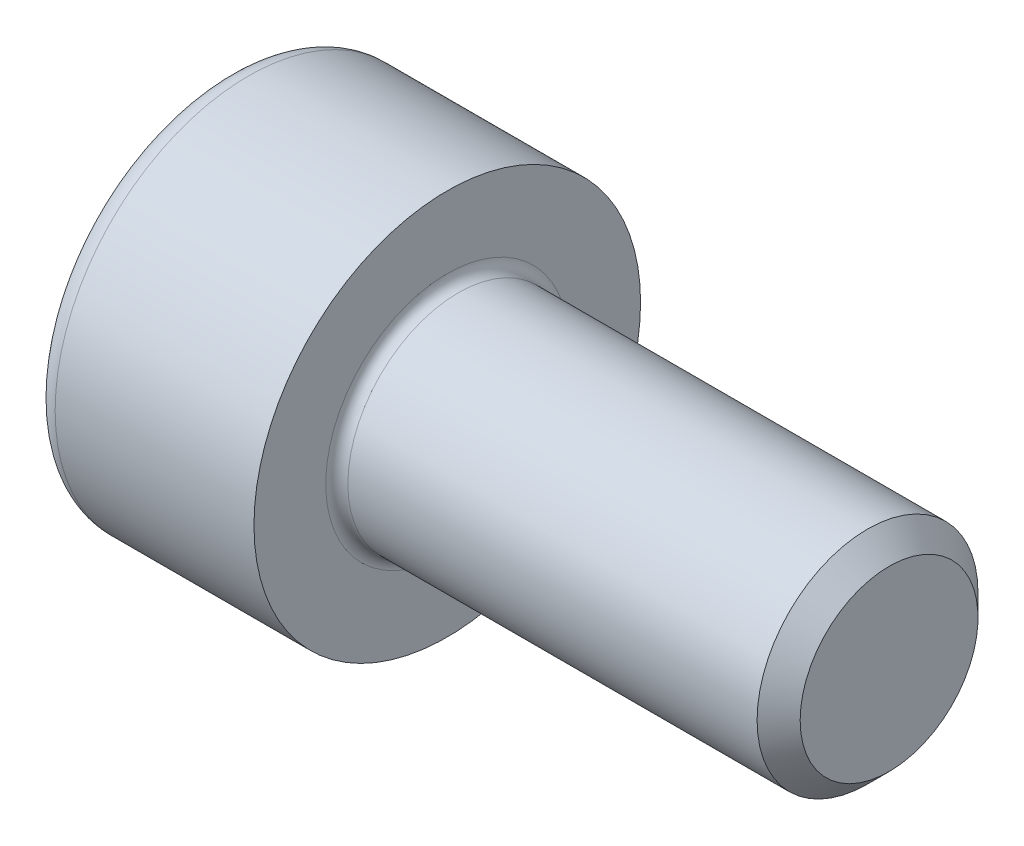
SolidWorks part; units mm, degrees
material "Ст3пс ГОСТ 380-2005"
ref_plane "Plane1" through (0, 0, 0) normal (0, 0, 1) x (1, 0, 0)
ref_plane "Plane2" through (0, 0, 0) normal (0, 1, 0) x (1, 0, 0)
ref_plane "Plane3" through (0, 0, 0) normal (1, 0, 0) x (0, 0, -1)
sketch "BodySke" plane through (0, 0, 0) normal (0, 0, 1) x (1, 0, 0)
  line L0 (0, 0) -> (0, 3.5)
  line L1 (0, 3.5) -> (4, 3.5)
  line L2 (4, 3.5) -> (4, 2)
  line L3 (4, 2) -> (11.61, 2)
  line L4 (12, 1.61) -> (12, 0)
  line L5 (12, 0) -> (0, 0)
  line L6 (-31.75, 0) -> (127, 0) construction
  line L8 (12, 1.61) -> (11.61, 2)
  line L10 (12, -1.61) -> (11.61, -2) construction
  line L11 (4.7, 9.525) -> (4.7, 3.175) construction
  line L12 (4, 9.525) -> (4, 3.175) construction
  line L13 (-48, 9.525) -> (-48, 3.175) construction
  dimension "Diameter" = 4
  dimension "Head_ht" = 4
  dimension "Length" = 8
  dimension "Body_ch_ang" = 45
  dimension "Head_dia" = 7
  dimension "Minor_dia" = 3.22
  dimension "Advance" = 0.7
  dimension "Thread_nom" = 8
  dimension "Thread_length" = 60
revolve "Base-Revolve" add sketch "BodySke"
cosmetic thread "ThreadCosmetic"
fillet "Fillet1" radius 0.2 1 edges at (4, 0, 2)
fillet "Fillet2" radius 0.4 1 edges at (0, 0, 3.5)
sketch "Sketch2" plane through (0, 0, 0) normal (0, 0, 1) x (1, 0, 0)
  line L0 (0, 1.51) -> (2, 1.51)
  line L1 (2, 1.51) -> (2.8718, 0)
  line L2 (-31.75, 0) -> (127, 0) construction
  line L3 (2.8718, 0) -> (0, 0)
  line L4 (0, 0) -> (0, 1.51)
  line L6 (0, 0) -> (47.625, 0) construction
  dimension "D1" = 1.51
  dimension "D2" = 60
  dimension "Depth" = 2
revolve "Hex-PreBroach" cut sketch "Sketch2" angle 360 about L6
sketch "Sketch3" plane through (0, 0, 0) normal (-1, 0, 0) x (0, 0.5, 0.866)
  line L0 (0.8718, 1.51) -> (-0.8718, 1.51)
  line L1 (-0.8718, 1.51) -> (-1.7436, 0)
  line L2 (0.8718, 1.51) -> (1.7436, 0)
  line L3 (0.8718, -1.51) -> (1.7436, 0)
  line L4 (0.8718, -1.51) -> (-0.8718, -1.51)
  line L5 (-0.8718, -1.51) -> (-1.7436, 0)
  dimension "D1" = 1.51
  dimension "D2" = 1.51
  dimension "Hex_size" = 3.02
extrude "Hex" cut sketch "Sketch3" against normal blind 2
